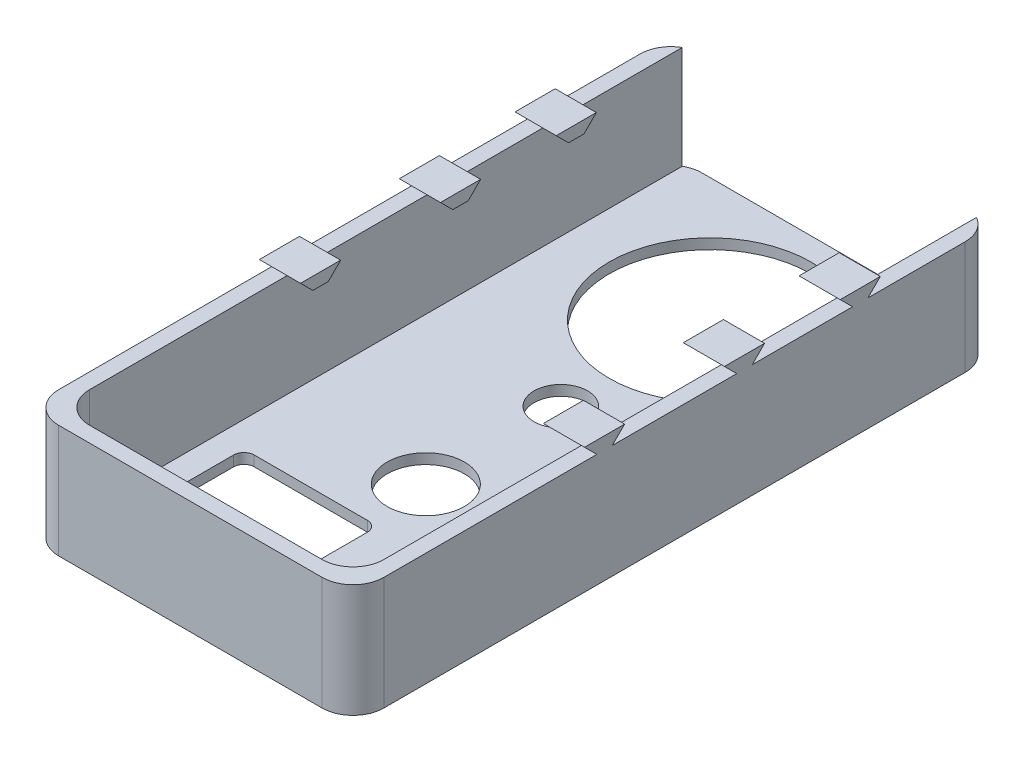
SolidWorks part; units mm, degrees
ref_plane "Front Plane" through (0, 0, 0) normal (0, 0, 1) x (1, 0, 0)
ref_plane "Top Plane" through (0, 0, 0) normal (0, 1, 0) x (1, 0, 0)
ref_plane "Right Plane" through (0, 0, 0) normal (1, 0, 0) x (0, 0, -1)
sketch "Sketch1" plane through (0, 0, 0) normal (0, 1, 0) x (1, 0, 0)
  line L1 (0, 0) -> (80.264, 0)
  line L2 (0, 0) -> (0, -158.75)
  line L3 (0, -158.75) -> (80.264, -158.75)
  line L4 (80.264, 0) -> (80.264, -158.75)
  dimension "D1" = 158.75
  dimension "D2" = 80.264
extrude "Boss-Extrude1" add sketch "Sketch1" along normal blind 2.54
sketch "Sketch2" plane through (0, 2.54, 0) normal (0, 1, 0) x (1, 0, 0)
  line L0 (80.264, 0) -> (0, 0) construction
  line L1 (11.43, -3.81) -> (68.834, -3.81)
  line L2 (3.81, -11.43) -> (3.81, -147.32)
  line L3 (11.43, -154.94) -> (68.834, -154.94)
  line L4 (76.454, -11.43) -> (76.454, -147.32)
  line L5 (0, -158.75) -> (80.264, -158.75) construction
  line L6 (80.264, -158.75) -> (80.264, 0) construction
  line L7 (0, 0) -> (0, -158.75) construction
  line L8 (3.81, -11.43) -> (3.81, 0)
  line L9 (0, 0) -> (80.264, 0)
  line L10 (0, 0) -> (0, -158.75)
  line L11 (0, -158.75) -> (80.264, -158.75)
  line L12 (80.264, 0) -> (80.264, -158.75)
  line L13 (76.454, -11.43) -> (76.454, 0)
  arc A0 (68.834, -154.94) -> (76.454, -147.32) centre (68.834, -147.32) ccw
  arc A1 (68.834, -3.81) -> (76.454, -11.43) centre (68.834, -11.43) cw
  arc A2 (11.43, -3.81) -> (3.81, -11.43) centre (11.43, -11.43) ccw
  arc A3 (3.81, -147.32) -> (11.43, -154.94) centre (11.43, -147.32) ccw
  dimension "D5" = 7.62
  dimension "D1" = 3.81
  dimension "D2" = 3.81
  dimension "D3" = 3.81
  dimension "D4" = 3.81
extrude "Boss-Extrude2" add sketch "Sketch2" along normal blind 25.4
fillet "Fillet1" radius 7.62 4 edges at (0, 13.97, 0) (80.264, 13.97, 0) (80.264, 13.97, 158.75) (0, 13.97, 158.75)
sketch "Sketch7" plane through (0, 0, 0) normal (0, -1, 0) x (1, 0, 0)
  line L1 (72.644, 0) -> (7.62, 0) construction
  line L5 (40.64, 148.59) -> (12.7, 148.59)
  line L6 (43.18, 146.05) -> (43.18, 118.11)
  line L7 (40.64, 115.57) -> (12.7, 115.57)
  line L8 (10.16, 146.05) -> (10.16, 118.11)
  line L10 (7.62, 158.75) -> (72.644, 158.75) construction
  line L12 (0, 7.62) -> (0, 151.13) construction
  circle A0 centre (40.132, 67.31) radius 6.604
  arc A1 (43.18, 118.11) -> (40.64, 115.57) centre (40.64, 118.11) cw
  arc A2 (12.7, 115.57) -> (10.16, 118.11) centre (12.7, 118.11) cw
  arc A3 (12.7, 148.59) -> (10.16, 146.05) centre (12.7, 146.05) ccw
  arc A4 (40.64, 148.59) -> (43.18, 146.05) centre (40.64, 146.05) cw
  circle A5 centre (40.132, 100.6475) radius 9.525
  circle A6 centre (40.132, 30.48) radius 24.892
  point P14 (43.18, 115.57)
  point P17 (10.16, 115.57)
  point P22 (43.18, 148.59)
  dimension "D1" = 32.512
  dimension "D3" = 13.208
  dimension "D8" = 2.54
  dimension "D9" = 19.05
  dimension "D12" = 49.784
  dimension "D13" = 30.48
  dimension "D2" = 83.82
  dimension "D4" = 10.16
  dimension "D5" = 10.16
  dimension "D6" = 33.02
  dimension "D7" = 33.02
  dimension "D10" = 33.3375
  dimension "D11" = 40.132
  dimension "D14" = 40.132
extrude "Cut-Extrude1" cut sketch "Sketch7" against normal through all
sketch "Sketch8" plane through (80.264, 0, 0) normal (1, 0, 0) x (0, 0, -1)
  line L0 (-98.552, 27.94) -> (-101.6, 30.988)
  line L1 (-151.13, 27.94) -> (-7.62, 27.94) construction
  line L2 (-101.6, 30.988) -> (-91.694, 30.988)
  line L3 (-91.694, 30.988) -> (-94.742, 27.94)
  line L4 (-94.742, 27.94) -> (-98.552, 27.94)
  line L5 (-64.008, 27.94) -> (-60.198, 27.94)
  line L6 (-60.198, 27.94) -> (-57.15, 30.988)
  line L7 (-57.15, 30.988) -> (-67.056, 30.988)
  line L8 (-67.056, 30.988) -> (-64.008, 27.94)
  line L9 (-38.481, 30.988) -> (-35.433, 27.94)
  line L10 (-35.433, 27.94) -> (-31.623, 27.94)
  line L11 (-31.623, 27.94) -> (-28.575, 30.988)
  line L12 (-28.575, 30.988) -> (-38.481, 30.988)
  line M11 (-7.62, 27.94) -> (-151.13, 27.94)
  dimension "D2" = 9.906
  dimension "D3" = 45
  dimension "D4" = 3.048
  dimension "D5" = 45
  dimension "D6" = 9.906
  dimension "D7" = 45
  dimension "D8" = 45
  dimension "D9" = 3.048
  dimension "D10" = 57.15
  dimension "D11" = 45
  dimension "D12" = 3.048
  dimension "D13" = 45
  dimension "D14" = 9.906
  dimension "D15" = 57.15
  dimension "D16" = 28.575
extrude "Boss-Extrude3" add sketch "Sketch8" against normal blind 10.16 contours L7 L8 L6 M11 | L11 L12 L9 M11 | L3 L4 L0 L2
ref_plane "Plane1" through (40.132, 0, 0) normal (1, 0, 0) x (0, 0, -1)
mirror "Mirror3" about plane through (40.132, 0, 0) normal (1, 0, 0) of "Boss-Extrude3"
